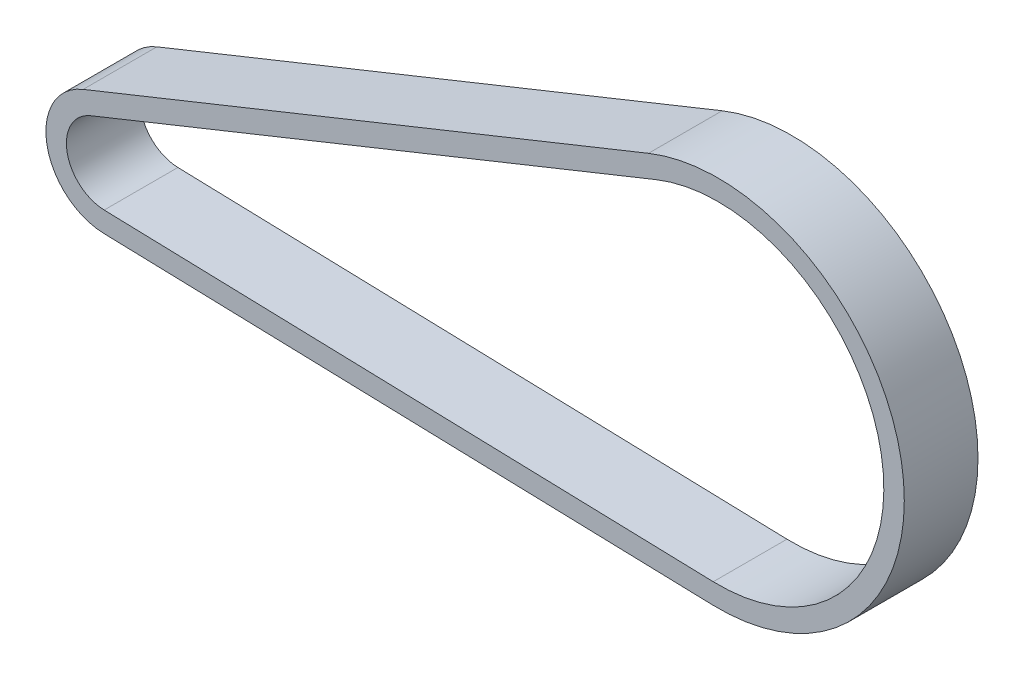
SolidWorks part; units mm, degrees
material "Beryllium"
ref_plane "Front Plane" through (0, 0, 0) normal (0, 0, 1) x (1, 0, 0)
ref_plane "Top Plane" through (0, 0, 0) normal (0, 1, 0) x (1, 0, 0)
ref_plane "Right Plane" through (0, 0, 0) normal (1, 0, 0) x (0, 0, -1)
sketch "Sketch1" plane through (0, 0, 0) normal (0, 0, 1) x (1, 0, 0)
  line L1 (-74.5029, 66.6476) -> (201.6235, 177.6676)
  line L2 (-66.2338, 20.3897) -> (231.2546, 11.9104)
  arc A0 (-74.5029, 66.6476) -> (-66.2338, 20.3897) centre (-65.55, 44.38) ccw
  arc A1 (231.2546, 11.9104) -> (201.6235, 177.6676) centre (233.7049, 97.8755) ccw
  circle A4 centre (-65.55, 44.38) radius 12 construction
  arc A5 (214.4372, 179.6358) -> (178.671, 161.3362) centre (233.7049, 97.8755) ccw construction
  point P2 (72.5955, 44.4755)
  dimension "D1" = 24
  dimension "D2" = 86
extrude "Extrude-Thin1" add sketch "Sketch1" along normal blind 28 and the other way blind 8 thin thin type mid plane wall 10
